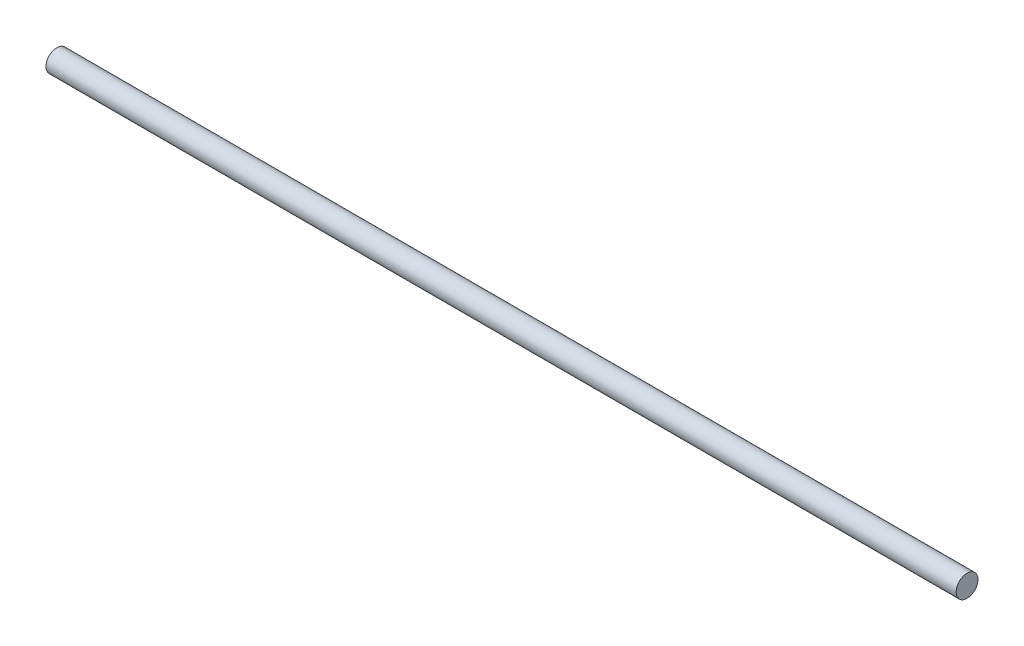
SolidWorks part; units mm, degrees
ref_plane "Front Plane" through (0, 0, 0) normal (0, 0, 1) x (1, 0, 0)
ref_plane "Top Plane" through (0, 0, 0) normal (0, 1, 0) x (1, 0, 0)
ref_plane "Right Plane" through (0, 0, 0) normal (1, 0, 0) x (0, 0, -1)
sketch "Sketch1" plane through (0, 0, 0) normal (1, 0, 0) x (0, 0, -1)
  circle A0 centre (0, 0) radius 6
  dimension "D1" = 12
extrude "Boss-Extrude1" add sketch "Sketch1" along normal blind 500
